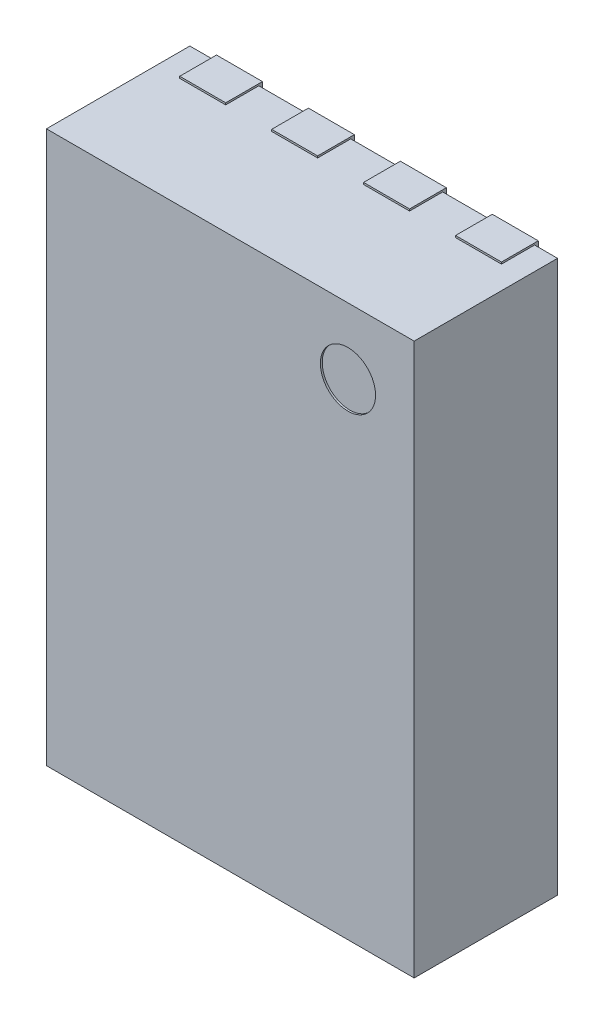
SolidWorks part; units mm, degrees
ref_plane "Front Plane" through (0, 0, 0) normal (0, 0, 1) x (1, 0, 0)
ref_plane "Top Plane" through (0, 0, 0) normal (0, 1, 0) x (1, 0, 0)
ref_plane "Right Plane" through (0, 0, 0) normal (1, 0, 0) x (0, 0, -1)
sketch "Sketch1" plane through (0, 0, 0) normal (0, 0, 1) x (1, 0, 0)
  line L1 (-1, 1.5) -> (1, 1.5)
  line L2 (-1, 1.5) -> (-1, -1.5)
  line L3 (-1, -1.5) -> (1, -1.5)
  line L4 (1, 1.5) -> (1, -1.5)
  line L5 (-1, 1.5) -> (1, -1.5) construction
  line L6 (-1, -1.5) -> (1, 1.5) construction
  point P0 (0, 0)
  dimension "D1" = 2
  dimension "D2" = 3
extrude "Boss-Extrude1" add sketch "Sketch1" along normal blind 0.78 contours L4 L3 L2 L1
sketch "Sketch2" plane through (0, 0, 0.78) normal (0, 0, 1) x (1, 0, 0)
  line L0 (0.64, 1.14) -> (0.64, 1.5) construction
  line L1 (-1, 1.5) -> (1, 1.5) construction
  line L2 (0.64, 1.14) -> (1, 1.14) construction
  line L4 (1, 1.5) -> (1, -1.5) construction
  circle A0 centre (0.64, 1.14) radius 0.15
  dimension "D1" = 0.3
  dimension "D2" = 0.36
extrude "Cut-Extrude1" cut sketch "Sketch2" against normal blind 0.01
sketch "Sketch3" plane through (0, 0, 0) normal (0, 0, -1) x (-1, 0, 0)
  line L1 (0.735, -0.75) -> (-0.735, -0.75)
  line L2 (0.75, -0.735) -> (0.75, 0.735)
  line L3 (0.735, 0.75) -> (-0.735, 0.75)
  line L4 (-0.75, -0.735) -> (-0.75, 0.735)
  line L5 (0.75, -0.75) -> (-0.75, 0.75) construction
  line L6 (0.75, 0.75) -> (-0.75, -0.75) construction
  arc A0 (-0.735, -0.75) -> (-0.75, -0.735) centre (-0.735, -0.735) cw
  arc A1 (-0.735, 0.75) -> (-0.75, 0.735) centre (-0.735, 0.735) ccw
  arc A2 (0.75, 0.735) -> (0.735, 0.75) centre (0.735, 0.735) ccw
  arc A3 (0.75, -0.735) -> (0.735, -0.75) centre (0.735, -0.735) cw
  point P0 (0, 0)
  dimension "D3" = 0.015
  dimension "D1" = 1.5
  dimension "D2" = 1.5
extrude "Boss-Extrude2" add sketch "Sketch3" along normal blind 0.02
sketch "Sketch6" plane through (0, 0, 0) normal (0, 0, -1) x (-1, 0, 0)
  line L0 (-0.875, 1.51) -> (-0.625, 1.51)
  line L1 (-0.625, 1.51) -> (-0.625, 1.5)
  line L2 (1, 1.5) -> (-1, 1.5) construction
  line L3 (-0.625, 1.5) -> (-0.625, 1.225)
  line L4 (-0.875, 1.51) -> (-0.875, 1.5)
  line L5 (-0.875, 1.5) -> (-0.875, 1.225)
  arc A0 (-0.875, 1.225) -> (-0.625, 1.225) centre (-0.75, 1.225) ccw
  point P9 (-0.75, 1.1)
  dimension "D1" = 0.01
  dimension "D2" = 0.25
  dimension "D3" = 0.4
  dimension "D4" = 0.75
extrude "Boss-Extrude4" add sketch "Sketch6" along normal blind 0.02 and the other way blind 0.18
pattern_linear "LPattern2" count 4 spacing 0.5 along (-1, 0, 0) of "Boss-Extrude4"
mirror "Mirror2" about plane through (0, 0, 0) normal (0, 1, 0) of "LPattern2", "Boss-Extrude4"
sketch "Sketch7" plane through (0, 0, -0.02) normal (0, 0, -1) x (-1, 0, 0)
  line L0 (-0.75, 0.4672) -> (-0.4672, 0.75)
  line L1 (-0.75, 0.735) -> (-0.75, -0.735) construction
  line L2 (0.735, 0.75) -> (-0.735, 0.75) construction
  line L3 (-0.4672, 0.75) -> (-0.75, 0.75)
  line L4 (-0.75, 0.75) -> (-0.75, 0.4672)
  dimension "D1" = 45
  dimension "D2" = 0.2
extrude "Cut-Extrude2" cut sketch "Sketch7" against normal up to surface (0.02 mm away) up to face at (0, 0, 0)
equation "\"E\"= 3"
equation "\"D\" = 2"
equation "\"H\"= \"A\" - \"A1\""
equation "\"D1@Boss-Extrude1\"=\"H\""
equation "\"D2@Sketch1\"=\"E\""
equation "\"D1@Sketch1\"=\"D\""
equation "\"D2\" = 1.5"
equation "\"E2\"= 1.5"
equation "\"L\"= 0.4"
equation "\"b\"= 0.25"
equation "\"e_\"= 0.5"
equation "\"A3\"= 0.2"
equation "\"K\"= 0.2"
equation "\"A1\" = 0.02"
equation "\"D1@Sketch3\"=\"D2\""
equation "\"D2@Sketch3\"=\"E2\""
equation "\"GND_R\"= ( \"D2\" + \"E2\" ) / 2 * 0.01"
equation "\"D3@Sketch3\"=\"GND_R\""
equation "\"D1@Boss-Extrude2\"=\"A1\""
equation "\"Px\"= 4"
equation "\"Py\"= 4"
equation "\"P\"= 2 * \"Px\" + 2 * \"Py\""
equation "\"D2@Sketch6\"=\"b\""
equation "\"D3@Sketch6\"=\"L\""
equation "\"D4@Sketch6\"=(\"Px\"/2-1)*\"e_\"+\"e_\"/2"
equation "\"D1@Boss-Extrude4\"=\"A1\""
equation "\"D2@Boss-Extrude4\"=\"A3\"-\"A1\""
equation "\"D3@LPattern2\"=\"e_\""
equation "\"D1@LPattern2\"=\"Px\""
equation "\"A\"= 0.8"
equation "\"D2@Sketch2\"=\"D1@Sketch2\"*1.2"
